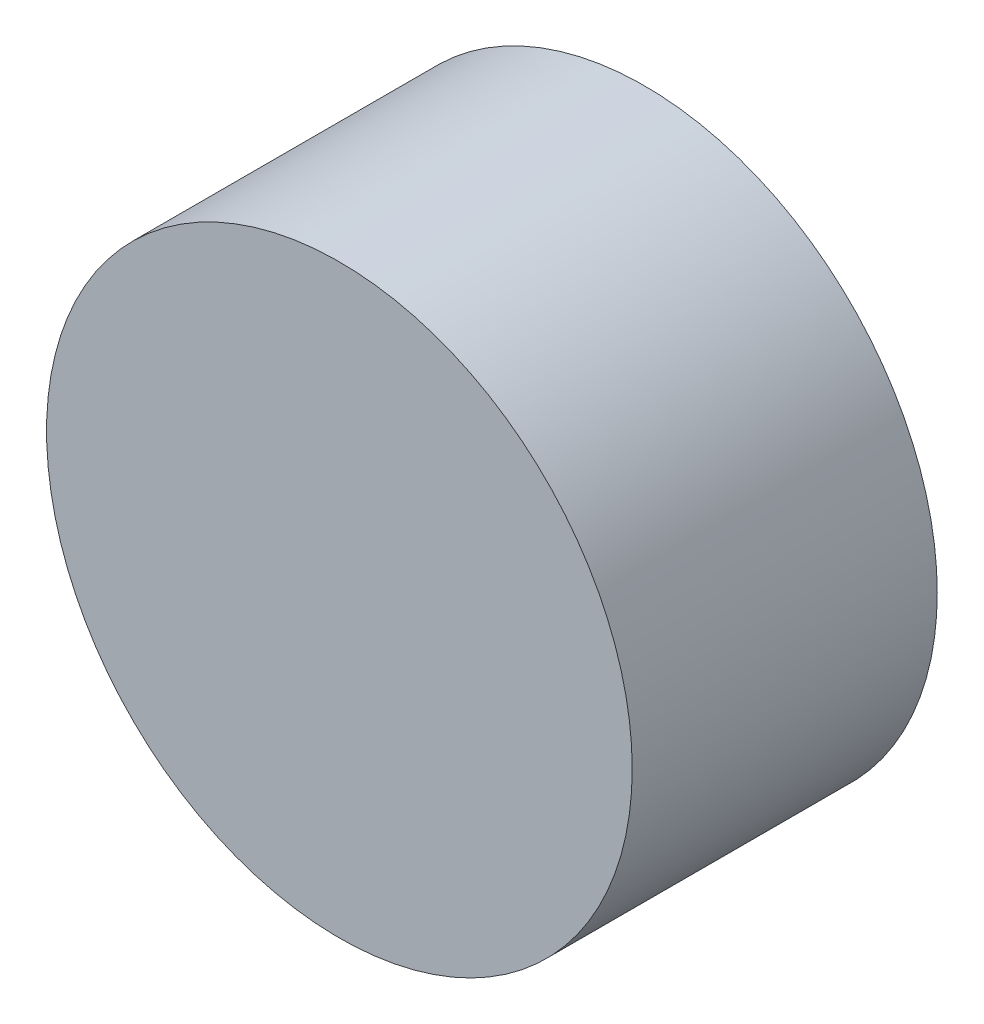
SolidWorks part; units mm, degrees
ref_plane "正面" through (0, 0, 0) normal (0, 0, 1) x (1, 0, 0)
ref_plane "平面" through (0, 0, 0) normal (0, 1, 0) x (1, 0, 0)
ref_plane "右側面" through (0, 0, 0) normal (1, 0, 0) x (0, 0, -1)
sketch "ｽｹｯﾁ1" plane through (0, 0, 0) normal (0, 0, 1) x (1, 0, 0)
  circle A0 centre (0, 0) radius 24
  dimension "D1" = 48
extrude "ﾎﾞｽ - 押し出し1" add sketch "ｽｹｯﾁ1" along normal blind 25 contours A0
